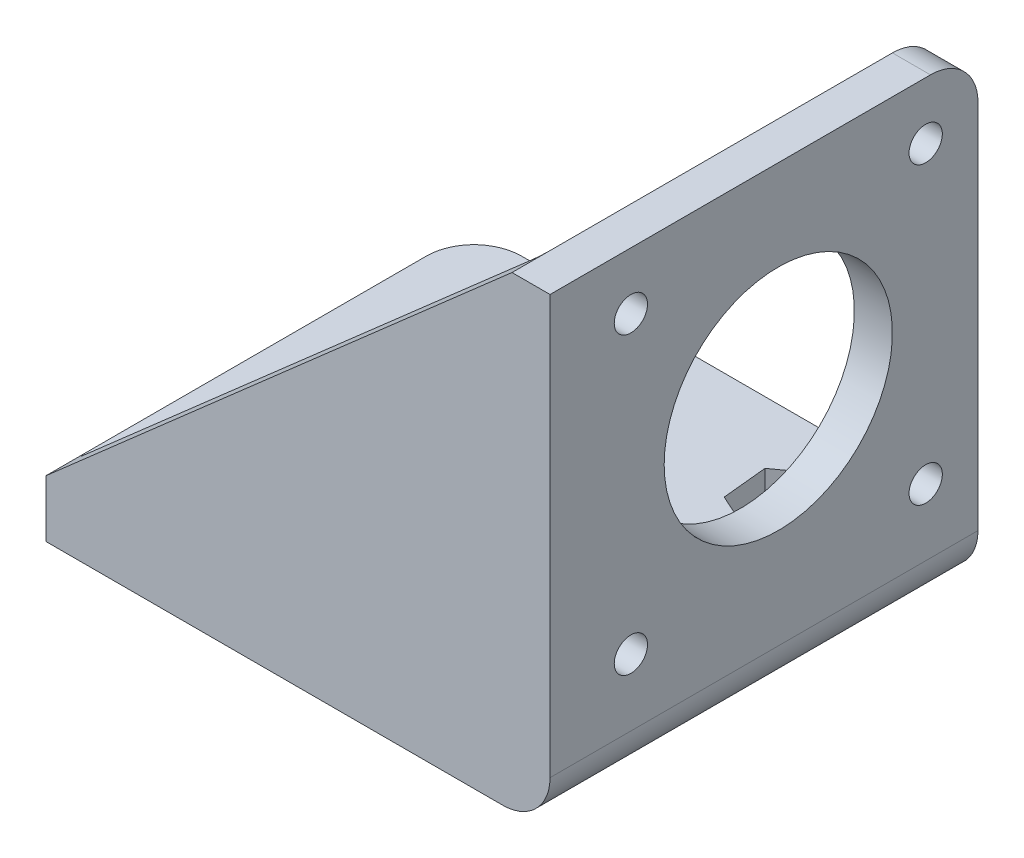
SolidWorks part; units mm, degrees
material "ABS"
ref_plane "Plano frontal" through (0, 0, 0) normal (0, 0, 1) x (1, 0, 0)
ref_plane "Plano superior" through (0, 0, 0) normal (0, 1, 0) x (1, 0, 0)
ref_plane "Plano direito" through (0, 0, 0) normal (1, 0, 0) x (0, 0, -1)
sketch "Esboço1" plane through (0, 0, 0) normal (0, 1, 0) x (1, 0, 0)
  line L1 (-26.5, 22.5) -> (26.5, 22.5)
  line L2 (-26.5, 22.5) -> (-26.5, -22.5)
  line L3 (-26.5, -22.5) -> (26.5, -22.5)
  line L4 (26.5, 22.5) -> (26.5, -22.5)
  line L5 (-26.5, 22.5) -> (26.5, -22.5) construction
  line L6 (-26.5, -22.5) -> (26.5, 22.5) construction
  point P0 (0, 0)
  dimension "D1" = 45
  dimension "D2" = 53
extrude "Ressalto-extrusão1" add sketch "Esboço1" along normal blind 6
sketch "Esboço2" plane through (0, 6, 0) normal (0, 1, 0) x (1, 0, 0)
  line L0 (-26.5, -22.5) -> (26.5, -22.5) construction
  line L1 (26.5, 22.5) -> (22.5, 22.5)
  line L2 (26.5, 22.5) -> (26.5, -22.5)
  line L3 (26.5, -22.5) -> (22.5, -22.5)
  line L4 (22.5, 22.5) -> (22.5, -22.5)
  dimension "D1" = 4
extrude "Ressalto-extrusão2" add sketch "Esboço2" along normal blind 43
sketch "Esboço3" plane through (0, 0, 22.5) normal (0, 0, 1) x (1, 0, 0)
  line L0 (-26.5, 6) -> (22.5, 49)
  line L1 (22.5, 6) -> (-26.5, 6)
  line L2 (22.5, 6) -> (22.5, 49)
extrude "Ressalto-extrusão3" add sketch "Esboço3" against normal blind 3
sketch "Esboço4" plane through (22.5, 0, 0) normal (-1, 0, 0) x (0, 0, 1)
  line L0 (-22.5, 27.5) -> (19.5, 27.5) construction
  line L1 (-22.5, 49) -> (-22.5, 6) construction
  line L2 (19.5, 6) -> (19.5, 49) construction
  line L3 (-1.5, 49) -> (-1.5, 6) construction
  line L4 (-22.5, 49) -> (19.5, 49) construction
  line L5 (-22.5, 6) -> (19.5, 6) construction
  circle A0 centre (-1.5, 27.5) radius 12
  circle A1 centre (-17, 43) radius 1.75
  circle A2 centre (14, 43) radius 1.75
  circle A3 centre (14, 12) radius 1.75
  circle A4 centre (-17, 12) radius 1.75
  point P15 (-1.5, 27.5)
  point P26 (-1.5, 27.5)
  dimension "D1" = 24
  dimension "D2" = 3.5
  dimension "D3" = 15.5
  dimension "D4" = 15.5
  dimension "D5" = 4
extrude "Corte-extrusão1" cut sketch "Esboço4" against normal through all
sketch "Esboço5" plane through (0, 6, 0) normal (0, 1, 0) x (1, 0, 0)
  line L0 (0, 22.5) -> (0, -19.5) construction
  line L1 (22.5, 22.5) -> (-26.5, 22.5) construction
  line L2 (-26.5, -19.5) -> (22.5, -19.5) construction
  circle A0 centre (-15, 14) radius 2.75
  circle A1 centre (-15, -11) radius 2.75
  circle A2 centre (15, -11) radius 2.75
  circle A3 centre (15, 14) radius 2.75
  dimension "D1" = 5.5
  dimension "D4" = 5.5
  dimension "D2" = 15
  dimension "D3" = 8.5
  dimension "D5" = 25
extrude "Corte-extrusão2" cut sketch "Esboço5" against normal through all
sketch "Esboço7" plane through (0, 6, 0) normal (0, 1, 0) x (1, 0, 0)
  line L0 (15.4731, 9.2314) -> (19.3663, 12.0254)
  line L1 (-14.5269, 9.2314) -> (-10.6337, 12.0254)
  line L2 (-10.6337, 12.0254) -> (-11.1068, 16.794)
  line L3 (-11.1068, 16.794) -> (-15.4731, 18.7686)
  line L4 (-15.4731, 18.7686) -> (-19.3663, 15.9746)
  line L5 (-19.3663, 15.9746) -> (-18.8932, 11.206)
  line L6 (-18.8932, 11.206) -> (-14.5269, 9.2314)
  line L7 (19.3663, 12.0254) -> (18.8932, 16.794)
  line L8 (18.8932, 16.794) -> (14.5269, 18.7686)
  line L9 (14.5269, 18.7686) -> (10.6337, 15.9746)
  line L10 (10.6337, 15.9746) -> (11.1068, 11.206)
  line L11 (11.1068, 11.206) -> (15.4731, 9.2314)
  line L12 (15.4731, -15.7686) -> (19.3663, -12.9746)
  line L13 (19.3663, -12.9746) -> (18.8932, -8.206)
  line L14 (18.8932, -8.206) -> (14.5269, -6.2314)
  line L15 (14.5269, -6.2314) -> (10.6337, -9.0254)
  line L16 (10.6337, -9.0254) -> (11.1068, -13.794)
  line L17 (11.1068, -13.794) -> (15.4731, -15.7686)
  line L18 (-14.5269, -15.7686) -> (-10.6337, -12.9746)
  line L19 (-10.6337, -12.9746) -> (-11.1068, -8.206)
  line L20 (-11.1068, -8.206) -> (-15.4731, -6.2314)
  line L21 (-15.4731, -6.2314) -> (-19.3663, -9.0254)
  line L22 (-19.3663, -9.0254) -> (-18.8932, -13.794)
  line L23 (-18.8932, -13.794) -> (-14.5269, -15.7686)
  circle A0 centre (-15, 14) radius 4.15 construction
  circle A1 centre (15, 14) radius 4.15 construction
  circle A2 centre (15, -11) radius 4.15 construction
  circle A3 centre (-15, -11) radius 4.15 construction
  dimension "D1" = 8.3
  dimension "D2" = 2
  dimension "D3" = 2
fillet "Filete1" radius 5 2 edges at (-26.5, 3, -22.5) (24.5, 49, -22.5)
fillet "Filete2" radius 1 3 edges at (22.5, 6, -1.5) (22.5, 27.5, 19.5) (-2, 6, 19.5)
extrude "Corte-extrusão4" cut sketch "Esboço7" against normal blind 4
fillet "Filete3" radius 5 1 edges at (26.5, 0, 0)
